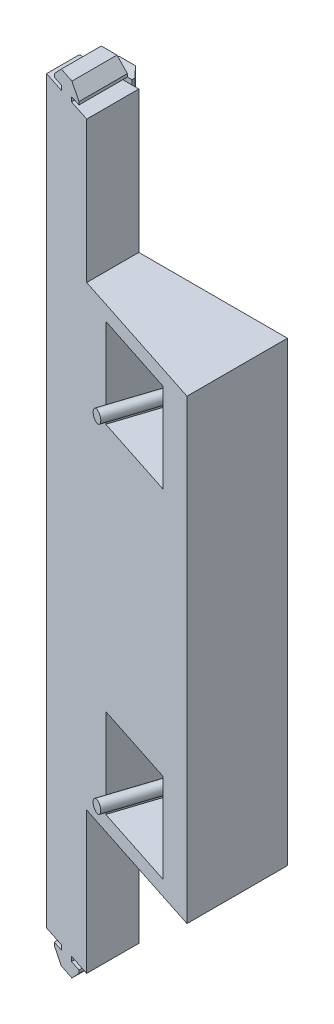
SolidWorks part; units mm, degrees
ref_plane "Plan de face" through (0, 0, 0) normal (0, 0, 1) x (1, 0, 0)
ref_plane "Plan de dessus" through (0, 0, 0) normal (0, 1, 0) x (1, 0, 0)
ref_plane "Plan de droite" through (0, 0, 0) normal (1, 0, 0) x (0, 0, -1)
sketch "Esquisse1" plane through (0, 0, 0) normal (0, 0, 1) x (1, 0, 0)
  line L0 (-193.167, -9.165) -> (-193.167, -270.565)
  line L1 (-193.167, -270.565) -> (-123.167, -270.565)
  line L2 (-123.167, -270.565) -> (-123.167, -9.165)
  line L3 (-123.167, -9.165) -> (-193.167, -9.165)
extrude "Boss.-Extru.1" add sketch "Esquisse1" along normal blind 40
sketch "Esquisse3" plane through (0, 0, 40) normal (0, 0, 1) x (1, 0, 0)
  line L0 (-173.167, -9.165) -> (-173.167, -63.005)
  line L1 (-123.167, -9.165) -> (-193.167, -9.165) construction
  line L2 (-173.167, -63.005) -> (-123.167, -63.005)
  line L3 (-123.167, -270.565) -> (-123.167, -9.165) construction
extrude "Enlèv. mat.-Extru.1" cut sketch "Esquisse3" against normal blind 40 and the other way through all
sketch "Esquisse4" plane through (0, 0, 40) normal (0, 0, 1) x (1, 0, 0)
  line L0 (-173.167, -270.565) -> (-173.167, -216.725)
  line L1 (-193.167, -270.565) -> (-123.167, -270.565) construction
  line L2 (-173.167, -216.725) -> (-123.167, -216.725)
  line L3 (-123.167, -270.565) -> (-123.167, -63.005) construction
extrude "Enlèv. mat.-Extru.2" cut sketch "Esquisse4" against normal blind 40 and the other way through all flip side to cut
sketch "Esquisse6" plane through (0, -63.005, 0) normal (0, 1, 0) x (1, 0, 0)
  line L0 (-123.167, -6.2) -> (-173.167, -6.2)
  line L1 (-123.167, -40) -> (-123.167, 0) construction
  line L2 (-173.167, -40) -> (-173.167, 0) construction
  line L3 (-173.167, -6.2) -> (-173.167, 0)
extrude "Enlèv. mat.-Extru.3" cut sketch "Esquisse6" against normal blind 165 and the other way through all flip side to cut
sketch "Esquisse7" plane through (0, -9.165, 0) normal (0, 1, 0) x (1, 0, 0)
  line L0 (-173.167, -6.2) -> (-180.717, -6.2)
  line L1 (-180.717, -6.2) -> (-180.717, -4.65)
  line L2 (-180.717, -4.65) -> (-177.017, -4.65)
  line L3 (-177.017, -4.65) -> (-177.017, -3.65)
  line L4 (-177.017, -3.65) -> (-180.5214, 0)
  line L5 (-173.167, 0) -> (-193.167, 0) construction
  dimension "D1" = 7.55
  dimension "D2" = 1.55
  dimension "D3" = 3.7
  dimension "D4" = 1
  dimension "D5" = 5.06
extrude "Enlèv. mat.-Extru.4" cut sketch "Esquisse7" against normal blind 261.4 and the other way through all flip side to cut
sketch "Esquisse8" plane through (0, -9.165, 0) normal (0, 1, 0) x (1, 0, 0)
  line L0 (-193.167, -40) -> (-193.167, 0) construction
  line L1 (-193.167, -6.2) -> (-185.617, -6.2)
  line L2 (-185.617, -6.2) -> (-185.617, -4.65)
  line L3 (-185.617, -4.65) -> (-189.317, -4.65)
  line L4 (-189.317, -4.65) -> (-189.317, -3.65)
  line L5 (-189.317, -3.65) -> (-185.8125, 0)
  line L6 (-180.5214, 0) -> (-193.167, 0) construction
  dimension "D1" = 6.2
  dimension "D2" = 1.55
  dimension "D3" = 3.7
  dimension "D4" = 7.55
  dimension "D5" = 1
  dimension "D6" = 5.06
extrude "Enlèv. mat.-Extru.5" cut sketch "Esquisse8" against normal blind 261.4 and the other way through all
sketch "Esquisse9" plane through (0, 0, 40) normal (0, 0, 1) x (1, 0, 0)
  line L0 (-193.167, -15.365) -> (-185.617, -15.365)
  line L1 (-193.167, -9.165) -> (-193.167, -270.565) construction
  line L2 (-185.617, -15.365) -> (-185.617, -13.815)
  line L3 (-185.617, -13.815) -> (-189.317, -13.815)
  line L4 (-189.317, -13.815) -> (-189.317, -12.815)
  line L5 (-189.317, -12.815) -> (-185.8125, -9.165)
  line L6 (-173.167, -9.165) -> (-193.167, -9.165) construction
  dimension "D1" = 6.2
  dimension "D2" = 7.55
  dimension "D3" = 1.55
  dimension "D4" = 3.7
  dimension "D5" = 1
  dimension "D6" = 5.06
extrude "Enlèv. mat.-Extru.6" cut sketch "Esquisse9" against normal blind 40 and the other way through all
sketch "Esquisse10" plane through (0, 0, 40) normal (0, 0, 1) x (1, 0, 0)
  line L0 (-173.167, -15.365) -> (-180.717, -15.365)
  line L1 (-173.167, -9.165) -> (-173.167, -63.005) construction
  line L2 (-180.717, -15.365) -> (-180.717, -13.815)
  line L3 (-180.717, -13.815) -> (-177.017, -13.815)
  line L4 (-177.017, -13.815) -> (-177.017, -12.815)
  line L5 (-177.017, -12.815) -> (-180.5214, -9.165)
  line L6 (-173.167, -9.165) -> (-185.8125, -9.165) construction
  dimension "D1" = 6.2
  dimension "D2" = 1.55
  dimension "D3" = 7.55
  dimension "D4" = 3.7
  dimension "D5" = 1
  dimension "D6" = 5.06
extrude "Enlèv. mat.-Extru.8" cut sketch "Esquisse10" against normal blind 40 and the other way through all flip side to cut
sketch "Esquisse11" plane through (-185.617, 0, 0) normal (-1, 0, 0) x (0, 0, 1)
  line L0 (0, -15.365) -> (6.2, -15.365)
  line L1 (6.2, -15.365) -> (6.2, -9.165)
  line L2 (6.2, -9.165) -> (6.2, -13.815) construction
extrude "Enlèv. mat.-Extru.9" cut sketch "Esquisse11" against normal blind 40 and the other way through all
sketch "Esquisse12" plane through (0, 0, 40) normal (0, 0, 1) x (1, 0, 0)
  line L0 (-173.167, -264.365) -> (-180.717, -264.365)
  line L1 (-173.167, -270.565) -> (-173.167, -216.725) construction
  line L2 (-180.717, -264.365) -> (-180.717, -265.915)
  line L3 (-180.717, -265.915) -> (-177.017, -265.915)
  line L4 (-177.017, -265.915) -> (-177.017, -266.915)
  line L5 (-177.017, -266.915) -> (-180.5214, -270.565)
  line L6 (-193.167, -270.565) -> (-173.167, -270.565) construction
  dimension "D1" = 6.2
  dimension "D2" = 7.55
  dimension "D3" = 1.55
  dimension "D4" = 3.7
  dimension "D5" = 1
  dimension "D6" = 5.06
extrude "Enlèv. mat.-Extru.10" cut sketch "Esquisse12" against normal blind 40 and the other way through all
sketch "Esquisse13" plane through (0, 0, 40) normal (0, 0, 1) x (1, 0, 0)
  line L0 (-193.167, -264.365) -> (-185.617, -264.365)
  line L1 (-193.167, -15.365) -> (-193.167, -270.565) construction
  line L2 (-185.617, -264.365) -> (-185.617, -265.915)
  line L3 (-185.617, -265.915) -> (-189.317, -265.915)
  line L4 (-189.317, -265.915) -> (-189.317, -266.915)
  line L5 (-189.317, -266.915) -> (-185.8125, -270.565)
  line L6 (-193.167, -270.565) -> (-180.5214, -270.565) construction
  dimension "D1" = 6.2
  dimension "D2" = 7.55
  dimension "D3" = 1.55
  dimension "D4" = 3.7
  dimension "D5" = 1
  dimension "D6" = 5.06
extrude "Enlèv. mat.-Extru.12" cut sketch "Esquisse13" against normal blind 40 and the other way through all flip side to cut
sketch "Esquisse16" plane through (-180.717, 0, 0) normal (1, 0, 0) x (0, 0, -1)
  line L0 (0, -264.365) -> (-6.2, -264.365)
  line L1 (-6.2, -264.365) -> (-6.2, -270.565)
extrude "Enlèv. mat.-Extru.14" cut sketch "Esquisse16" against normal blind 4.9 and the other way through all
sketch "Esquisse32" plane through (0, -264.365, 0) normal (0, -1, 0) x (-1, 0, 0)
  line L0 (193.167, -40) -> (123.167, -40)
  line L1 (123.167, -40) -> (193.167, -17.2556)
  line L2 (193.167, -40) -> (193.167, -6.2) construction
  dimension "D1" = 18
extrude "Enlèv. mat.-Extru.30" cut sketch "Esquisse32" against normal through all and the other way through all flip side to cut
sketch "Esquisse33" plane through (-23.5171, 0, 72.3782) normal (-0.309, 0, 0.9511) x (0.9511, 0, 0.309)
  line L0 (-147.3512, -68.005) -> (-147.3512, -98.005)
  line L1 (-147.3512, -98.005) -> (-117.3512, -98.005)
  line L2 (-117.3512, -98.005) -> (-117.3512, -68.005)
  line L3 (-117.3512, -68.005) -> (-147.3512, -68.005)
  line L4 (-104.7781, -63.005) -> (-157.3512, -63.005) construction
  line L5 (-157.3512, -63.005) -> (-157.3512, -15.365) construction
  dimension "D1" = 30
  dimension "D2" = 30
  dimension "D3" = 5
  dimension "D4" = 10
extrude "Enlèv. mat.-Extru.34" cut sketch "Esquisse33" against normal blind 20
sketch "Esquisse36" plane through (-23.5171, 0, 72.3782) normal (-0.309, 0, 0.9511) x (0.9511, 0, 0.309)
  line L0 (-147.3512, -211.725) -> (-117.3512, -211.725)
  line L1 (-117.3512, -211.725) -> (-117.3512, -181.725)
  line L2 (-117.3512, -181.725) -> (-147.3512, -181.725)
  line L3 (-147.3512, -181.725) -> (-147.3512, -211.725)
  line L4 (-157.3512, -264.365) -> (-157.3512, -216.725) construction
  line L5 (-104.7781, -216.725) -> (-157.3512, -216.725) construction
  dimension "D1" = 30
  dimension "D2" = 30
  dimension "D3" = 10
  dimension "D4" = 5
extrude "Enlèv. mat.-Extru.35" cut sketch "Esquisse36" against normal blind 20
sketch "Esquisse38" plane through (-17.3368, 0, 53.3571) normal (-0.309, 0, 0.9511) x (0.9511, 0, 0.309)
  circle A0 centre (-132.3512, -83.005) radius 2
extrude "Boss.-Extru.2" add sketch "Esquisse38" along normal blind 30
sketch "Esquisse39" plane through (-17.3368, 0, 53.3571) normal (-0.309, 0, 0.9511) x (0.9511, 0, 0.309)
  circle A1 centre (-132.3512, -196.725) radius 2
  point P1 (0, 0)
extrude "Boss.-Extru.3" add sketch "Esquisse39" along normal blind 30
